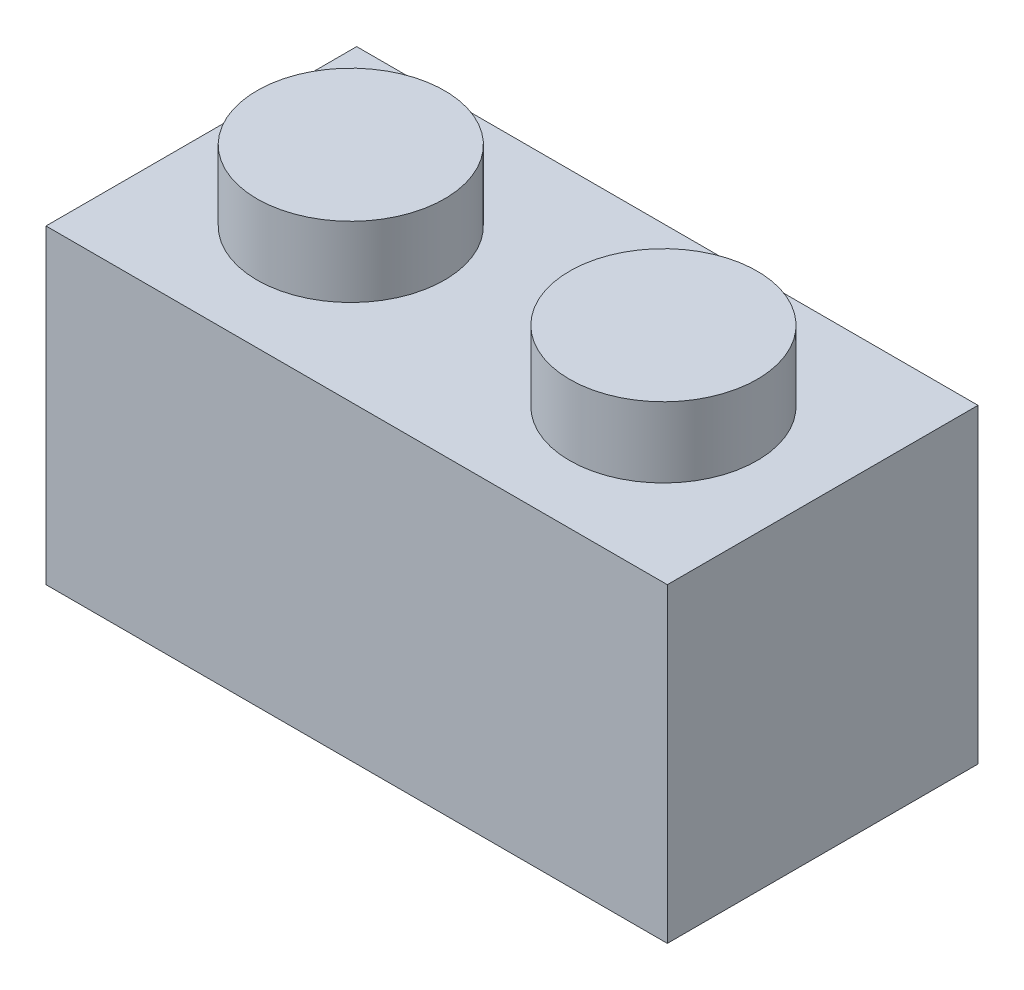
SolidWorks part; units mm, degrees
ref_plane "Front Plane" through (0, 0, 0) normal (0, 0, 1) x (1, 0, 0)
ref_plane "Top Plane" through (0, 0, 0) normal (0, 1, 0) x (1, 0, 0)
ref_plane "Right Plane" through (0, 0, 0) normal (1, 0, 0) x (0, 0, -1)
sketch "Sketch1" plane through (0, 0, 0) normal (0, 0, 1) x (1, 0, 0)
  line L1 (-7.95, -3.975) -> (7.95, -3.975)
  line L2 (-7.95, -3.975) -> (-7.95, 3.975)
  line L3 (-7.95, 3.975) -> (7.95, 3.975)
  line L4 (7.95, -3.975) -> (7.95, 3.975)
  line L5 (-7.95, -3.975) -> (7.95, 3.975) construction
  line L6 (-7.95, 3.975) -> (7.95, -3.975) construction
  point P0 (0, 0)
  dimension "D1" = 7.95
  dimension "D2" = 15.9
extrude "Boss-Extrude1" add sketch "Sketch1" against normal blind 7.95
sketch "Sketch2" plane through (0, 3.975, 0) normal (0, 1, 0) x (1, 0, 0)
  line L0 (7.95, 0) -> (-7.95, 0) construction
  line L1 (-7.95, 7.95) -> (-7.95, 0) construction
  circle A0 centre (-4.05, 3.9) radius 2.4
  dimension "D1" = 4.8
  dimension "D2" = 3.9
  dimension "D3" = 3.9
extrude "Boss-Extrude2" add sketch "Sketch2" along normal blind 1.8
pattern_linear "LPattern1" count 2 spacing 8 along (1, 0, 0) of "Boss-Extrude2"
shell "Shell1" thickness 1.2
